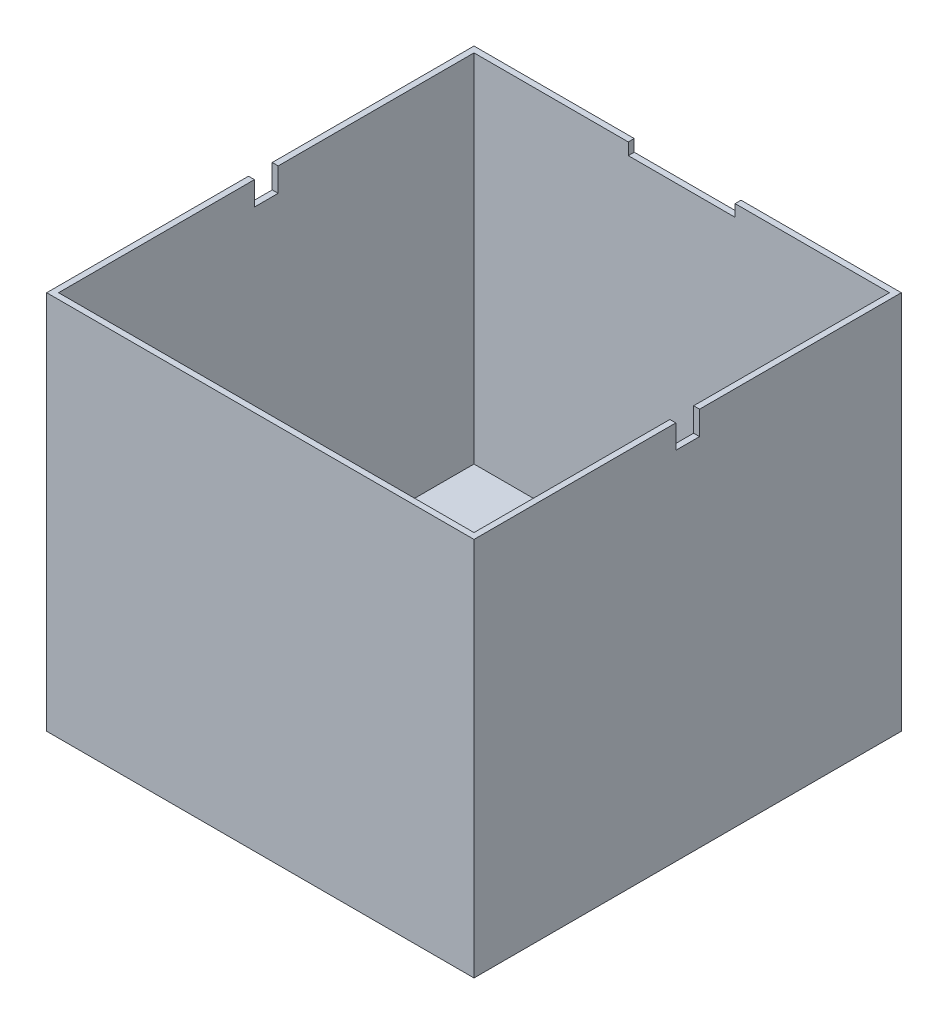
SolidWorks part; units mm, degrees
ref_plane "Front Plane" through (0, 0, 0) normal (0, 0, 1) x (1, 0, 0)
ref_plane "Top Plane" through (0, 0, 0) normal (0, 1, 0) x (1, 0, 0)
ref_plane "Right Plane" through (0, 0, 0) normal (1, 0, 0) x (0, 0, -1)
sketch "Sketch1" plane through (0, 0, 0) normal (0, 1, 0) x (1, 0, 0)
  line L1 (-90, 90) -> (90, 90)
  line L2 (-90, 90) -> (-90, -90)
  line L3 (-90, -90) -> (90, -90)
  line L4 (90, 90) -> (90, -90)
  line L5 (-90, 90) -> (90, -90) construction
  line L6 (-90, -90) -> (90, 90) construction
  point P0 (0, 0)
  dimension "D1" = 180
  dimension "D2" = 180
extrude "Boss-Extrude1" add sketch "Sketch1" against normal blind 5 and the other way blind 150
sketch "Sketch6" plane through (0, 150, 0) normal (0, 1, 0) x (1, 0, 0)
  line L1 (-87.5, 87.5) -> (87.5, 87.5)
  line L2 (-87.5, 87.5) -> (-87.5, -87.5)
  line L3 (-87.5, -87.5) -> (87.5, -87.5)
  line L4 (87.5, 87.5) -> (87.5, -87.5)
  line L5 (-87.5, 87.5) -> (87.5, -87.5) construction
  line L6 (-87.5, -87.5) -> (87.5, 87.5) construction
  point P0 (0, 0)
  dimension "D1" = 175
  dimension "D2" = 175
extrude "Cut-Extrude2" cut sketch "Sketch6" against normal blind 150
sketch "Sketch34" plane through (0, -5, 0) normal (0, -1, 0) x (1, 0, 0)
  line L4 (90, -90) -> (90, 90)
  line L5 (90, 90) -> (-90, 90)
  line L6 (-90, 90) -> (-90, -90)
  line L7 (-90, -90) -> (90, -90)
  line L8 (90, -90) -> (90, 90)
  line L9 (90, 90) -> (-90, 90)
  line L10 (-90, 90) -> (-90, -90)
  line L11 (-90, -90) -> (90, -90)
  dimension "D1" = 0
extrude "Boss-Extrude14" add sketch "Sketch34" along normal blind 5
sketch "Sketch35" plane through (0, -10, 0) normal (0, -1, 0) x (1, 0, 0)
  line L1 (-83.1, 83.1) -> (-67.9, 83.1)
  line L2 (-83.1, 83.1) -> (-83.1, 67.9)
  line L3 (-83.1, 67.9) -> (-67.9, 67.9)
  line L4 (-67.9, 83.1) -> (-67.9, 67.9)
  line L5 (-83.1, 83.1) -> (-67.9, 67.9) construction
  line L6 (-83.1, 67.9) -> (-67.9, 83.1) construction
  point P0 (-75.5, 75.5)
  dimension "D1" = 15.2
  dimension "D2" = 15.2
extrude "Cut-Extrude11" cut sketch "Sketch35" against normal blind 5 contours L3 L4 L1 L2
sketch "Sketch37" plane through (0, 0, 0) normal (0, 1, 0) x (1, 0, 0)
  line L1 (-62.6, -40.85) -> (-48.4, -40.85)
  line L2 (-62.6, -40.85) -> (-62.6, -26.65)
  line L3 (-62.6, -26.65) -> (-48.4, -26.65)
  line L4 (-48.4, -40.85) -> (-48.4, -26.65)
  dimension "D1" = 14.2
  dimension "D2" = 14.2
extrude "Cut-Extrude12" cut sketch "Sketch37" against normal blind 5
mirror "Mirror12" about plane through (0, 0, 0) normal (0, 0, 1) of "Cut-Extrude12", "Cut-Extrude11"
mirror "Mirror13" about plane through (0, 0, 0) normal (1, 0, 0) of "Cut-Extrude11", "Mirror12", "Cut-Extrude12"
sketch "Sketch15" plane through (90, 0, 0) normal (1, 0, 0) x (0, 0, -1)
  line L0 (-90, 150) -> (90, 150) construction
  line L1 (-4.9952, 150) -> (5.0048, 150)
  line L2 (-4.9952, 150) -> (-4.9952, 140)
  line L3 (-4.9952, 140) -> (5.0048, 140)
  line L4 (5.0048, 150) -> (5.0048, 140)
  dimension "D1" = 10
  dimension "D2" = 10
extrude "Cut-Extrude7" cut sketch "Sketch15" against normal blind 3
mirror "Mirror3" about plane through (0, 0, 0) normal (1, 0, 0) of "Cut-Extrude7"
sketch "FocalPoint" plane through (0, 0, 0) normal (0, 0, 1) x (1, 0, 0)
  line L0 (0, 0) -> (0, 87)
  point P3 (0, 0)
  dimension "D1" = 87
sketch "Sketch21" plane through (0, 0, 87.5) normal (0, 0, -1) x (-1, 0, 0)
  line L1 (-24.9967, 90.002) -> (25.0033, 90.002)
  line L2 (-24.9967, 90.002) -> (-24.9967, 87.002)
  line L3 (-24.9967, 87.002) -> (25.0033, 87.002)
  line L4 (25.0033, 90.002) -> (25.0033, 87.002)
  dimension "D1" = 3
  dimension "D2" = 50
extrude "Boss-Extrude7" add sketch "Sketch21" along normal blind 10
sketch "Sketch22" plane through (0, 90.002, 0) normal (0, 1, 0) x (1, 0, 0)
  line L0 (-87.5, -87.5) -> (87.5, -87.5) construction
  line L1 (-25.0033, -77.5) -> (-22.5033, -77.5)
  line L2 (-25.0033, -77.5) -> (-25.0033, -87.5)
  line L3 (-25.0033, -87.5) -> (-22.5033, -87.5)
  line L4 (-22.5033, -77.5) -> (-22.5033, -87.5)
  dimension "D1" = 2.5
extrude "Boss-Extrude8" add sketch "Sketch22" along normal blind 5
mirror "Mirror7" about plane through (0, 0, 0) normal (1, 0, 0) of "Boss-Extrude8"
sketch "Sketch30" plane through (0, 150, 0) normal (0, 1, 0) x (1, 0, 0)
  line L0 (87.5, 87.5) -> (-87.5, 87.5) construction
  line L1 (-22.4975, 87.5) -> (22.5025, 87.5)
  line L2 (-22.4975, 87.5) -> (-22.4975, 90)
  line L3 (-22.4975, 90) -> (22.5025, 90)
  line L4 (22.5025, 87.5) -> (22.5025, 90)
  line L5 (90, 90) -> (-90, 90) construction
  dimension "D1" = 45
  dimension "D2" = 2.5
extrude "Cut-Extrude9" cut sketch "Sketch30" against normal blind 5
sketch "Sketch38" plane through (0, 0, 0) normal (0, 1, 0) x (1, 0, 0)
  line L1 (-35.1, 35.1) -> (35.1, 35.1)
  line L2 (-35.1, 35.1) -> (-35.1, -35.1)
  line L3 (-35.1, -35.1) -> (35.1, -35.1)
  line L4 (35.1, 35.1) -> (35.1, -35.1)
  line L5 (-35.1, 35.1) -> (35.1, -35.1) construction
  line L6 (-35.1, -35.1) -> (35.1, 35.1) construction
  point P0 (0, 0)
  dimension "D1" = 70.2
  dimension "D2" = 70.2
extrude "Cut-Extrude13" cut sketch "Sketch38" against normal blind 5
sketch "Sketch7" plane through (0, -5, 0) normal (0, 1, 0) x (1, 0, 0)
  circle A0 centre (0, 0) radius 25.65
  dimension "D1" = 51.3
extrude "Cut-Extrude14" cut sketch "Sketch7" against normal blind 5 contours A0
sketch "Sketch39" plane through (0, -5, 0) normal (0, 1, 0) x (1, 0, 0)
  circle A0 centre (0, 0) radius 27.15
  dimension "D1" = 54.3
extrude "Cut-Extrude16" cut sketch "Sketch39" against normal blind 2 from offset 1.5
